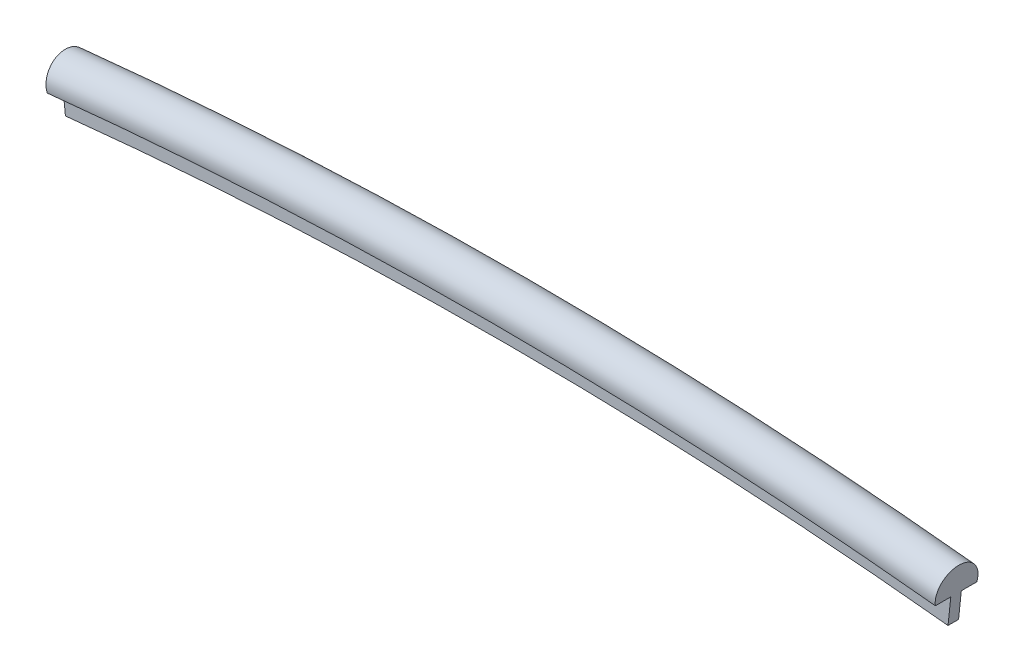
SolidWorks part; units mm, degrees
ref_plane "Front Plane" through (0, 0, 0) normal (0, 0, 1) x (1, 0, 0)
ref_plane "Top Plane" through (0, 0, 0) normal (0, 1, 0) x (1, 0, 0)
ref_plane "Right Plane" through (0, 0, 0) normal (1, 0, 0) x (0, 0, -1)
sketch "Sketch2" plane through (0, 0, 0) normal (1, 0, 0) x (0, 0, -1)
  line L0 (0, 241.3) -> (0, 0) construction
  line L2 (0, 241.3) -> (0, 239.8) construction
  line L3 (0, 239.8) -> (0.3, 239.8)
  line L4 (0, 239.8) -> (-0.3, 239.8)
  line L5 (-0.3, 239.8) -> (-0.3, 241.3)
  line L6 (0.3, 239.8) -> (0.3, 241.3)
  line L7 (0, 241.3) -> (0, 242.8) construction
  line L8 (-1.18, 241.3) -> (-0.3, 241.3)
  line L9 (0.3, 241.3) -> (1.18, 241.3)
  arc A0 (-1.18, 241.3) -> (1.18, 241.3) centre (0, 241.586) cw
  point P14 (0, 241.3)
ref_axis "Axis2" through (0, 0, 70.5976) along (0, 0, -1)
revolve "Revolve1" add sketch "Sketch2" angle 6.018 about axis through (0, 0, 70.5976) along (0, 0, -1)
